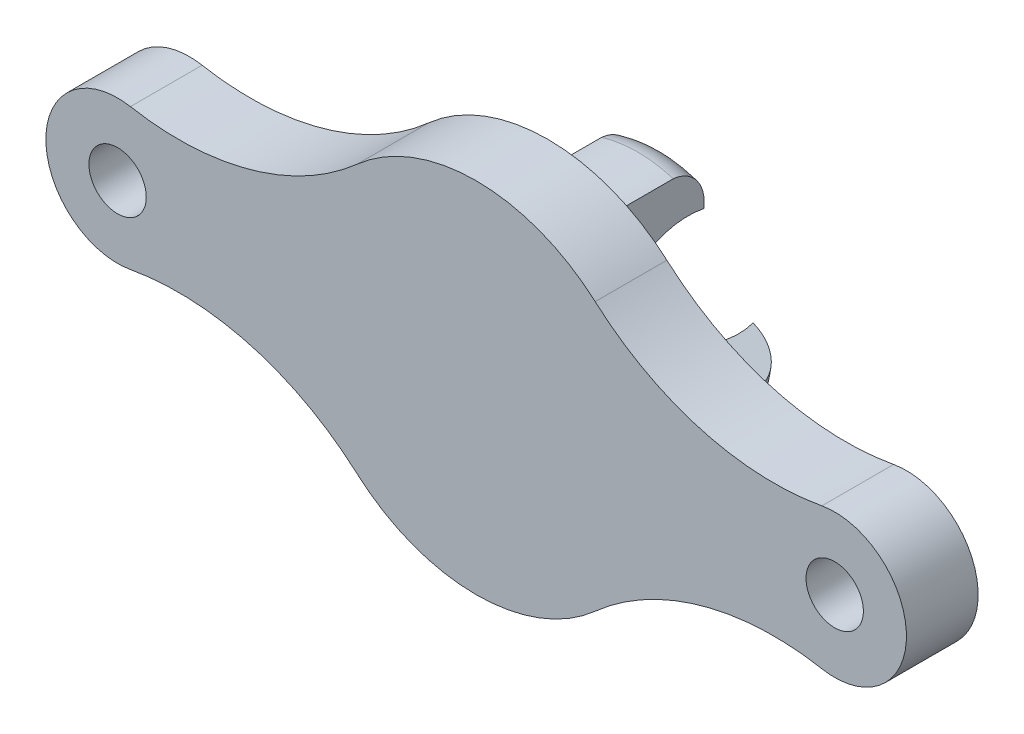
SolidWorks part; units mm, degrees
ref_plane "Plano frontal" through (0, 0, 0) normal (0, 0, 1) x (1, 0, 0)
ref_plane "Plano superior" through (0, 0, 0) normal (0, 1, 0) x (1, 0, 0)
ref_plane "Plano direito" through (0, 0, 0) normal (1, 0, 0) x (0, 0, -1)
sketch "Esboço1" plane through (0, 0, 0) normal (0, 1, 0) x (1, 0, 0)
  line L0 (0, 0) -> (6.8915, 0)
  line L1 (0, 0) -> (0, 19.1138) construction
  line L2 (6.8915, 5) -> (6.8915, 0)
  line L3 (0, 0.9958) -> (0, 0)
  arc A0 (0, 0.9958) -> (4.7436, 6.7035) centre (0, 5.8208) ccw
  arc A2 (6.8915, 5) -> (4.7436, 6.7035) centre (5, 4.8208) ccw
  dimension "D1" = 9.65
  dimension "D2" = 1
  dimension "D6" = 1.9
  dimension "D7" = 5
  dimension "D3" = 6.8915
  dimension "D4" = 5
revolve "Revolução1" add sketch "Esboço1" angle 360 about L1
sketch "Esboço3" plane through (0, 0, 0) normal (0, 0, 1) x (1, 0, 0)
  line L0 (-2, 19.3263) -> (-2, 1.7341)
  line L1 (-2, 1.7341) -> (-17.9373, -7.4673)
  line L2 (2, 19.3263) -> (2, 1.7341)
  line L3 (2, 1.7341) -> (17.9373, -7.4673)
  line L4 (0, -1.73) -> (-16.0273, -10.9833)
  line L5 (0, -1.73) -> (16.0273, -10.9833)
  arc A0 (-16.0273, -10.9833) -> (16.0273, -10.9833) centre (0, 0) ccw
  arc A1 (17.9373, -7.4673) -> (2, 19.3263) centre (0, 0) ccw
  arc A2 (-2, 19.3263) -> (-17.9373, -7.4673) centre (0, 0) ccw
  dimension "D8" = 38.8591
  dimension "D1" = 4
  dimension "D2" = 4
  dimension "D3" = 4
  dimension "D4" = 120
  dimension "D5" = 120
  dimension "D6" = 2
  dimension "D7" = 1.73
extrude "Corte-extrusão1" cut sketch "Esboço3" against normal through all
sketch "Esboço4" plane through (0, 0, 0) normal (0, 0, 1) x (1, 0, 0)
  arc A0 (-6.64, -7.4773) -> (6.64, -7.4773) centre (0, 0) ccw
  circle A1 centre (20, 0) radius 1.6
  circle A2 centre (-20, 0) radius 1.6
  arc A3 (-19.2842, 3.9354) -> (-19.2842, -3.9354) centre (-20, 0) ccw
  arc A4 (19.2842, -3.9354) -> (19.2842, 3.9354) centre (20, 0) ccw
  arc A5 (6.64, 7.4773) -> (19.2842, 3.9354) centre (16.6, 18.6933) ccw
  arc A6 (-19.2842, 3.9354) -> (-6.64, 7.4773) centre (-16.6, 18.6933) ccw
  arc A7 (-6.64, -7.4773) -> (-19.2842, -3.9354) centre (-16.6, -18.6933) ccw
  arc A8 (19.2842, -3.9354) -> (6.64, -7.4773) centre (16.6, -18.6933) ccw
  arc A9 (6.64, 7.4773) -> (-6.64, 7.4773) centre (0, 0) ccw
  dimension "D1" = 20
  dimension "D4" = 20
  dimension "D5" = 8
  dimension "D6" = 30
  dimension "D2" = 3.2
  dimension "D3" = 40
extrude "Ressalto-extrusão1" add sketch "Esboço4" along normal blind 4
